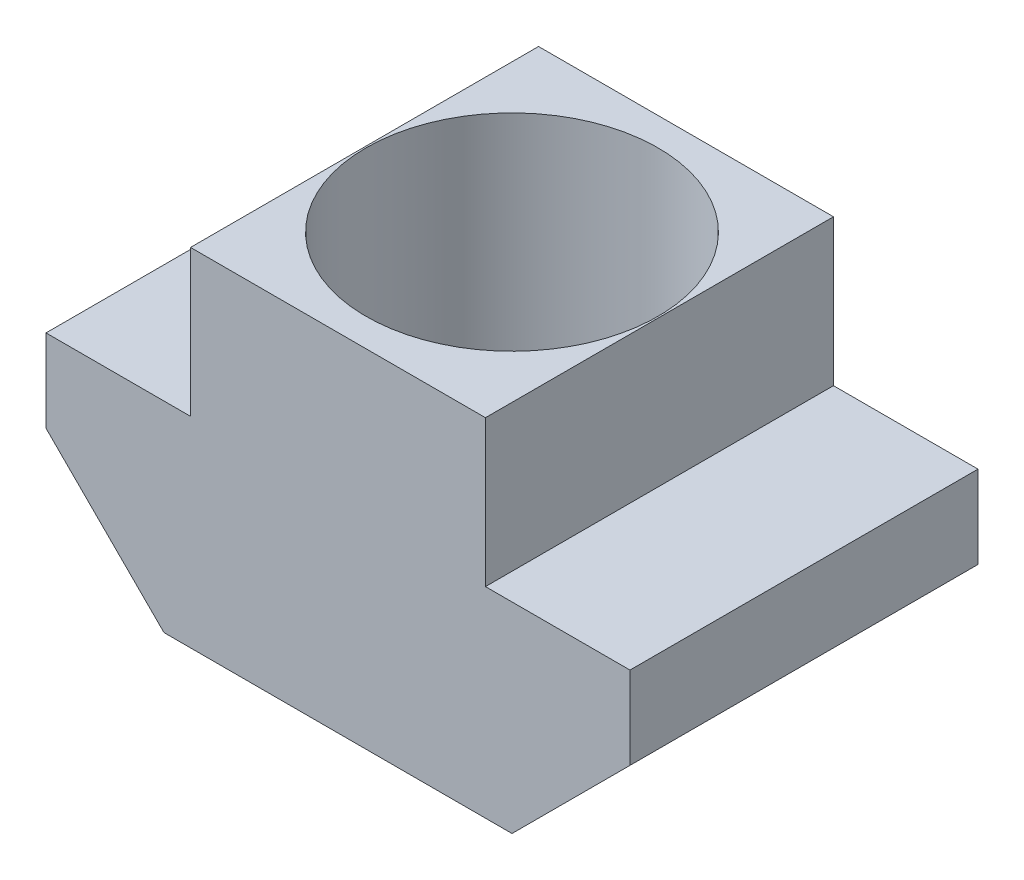
SolidWorks part; units mm, degrees
ref_plane "Front Plane" through (0, 0, 0) normal (0, 0, 1) x (1, 0, 0)
ref_plane "Top Plane" through (0, 0, 0) normal (0, 1, 0) x (1, 0, 0)
ref_plane "Right Plane" through (0, 0, 0) normal (1, 0, 0) x (0, 0, -1)
sketch "Sketch1" plane through (0, 0, 0) normal (0, 0, 1) x (1, 0, 0)
  line L12 (4.95, 0.3) -> (2.95, -1.7)
  line L13 (2.95, -1.7) -> (-2.95, -1.7)
  line L14 (4.95, 0.3) -> (4.95, 1.7)
  line L15 (4.95, 1.7) -> (2.5, 1.7)
  line L16 (-4.95, 0.3) -> (-4.95, 1.7)
  line L17 (4.95, -1.7) -> (-4.95, 1.7) construction
  line L18 (4.95, 1.7) -> (-4.95, -1.7) construction
  line L19 (-2.95, -1.7) -> (-4.95, 0.3)
  line L20 (0, 0) -> (0, 4.908) construction
  line L21 (-2.5, 1.7) -> (-4.95, 1.7)
  line L22 (2.5, 4.18) -> (-2.5, 4.18)
  line L23 (2.5, 4.18) -> (2.5, 1.7)
  line L25 (-2.5, 4.18) -> (-2.5, 1.7)
  line L26 (2.5, 4.18) -> (-2.5, 1.7) construction
  line L27 (2.5, 1.7) -> (-2.5, 4.18) construction
  point P0 (0, 0)
  point P14 (0, 2.94)
  dimension "D2" = 3.4
  dimension "D1" = 9.9
  dimension "D5" = 5
  dimension "D6" = 2.48
extrude "Boss-Extrude1" add sketch "Sketch1" along normal blind 5.9
sketch "Sketch2" plane through (0, 4.18, 0) normal (0, 1, 0) x (1, 0, 0)
  line L0 (2.5, 0) -> (-2.5, 0) construction
  circle A0 centre (0, -2.95) radius 2.475
  dimension "D2" = 4.95
  dimension "D1" = 2.95
extrude "Cut-Extrude7" cut sketch "Sketch2" against normal through all
sketch "Sketch3" plane through (0, 4.18, 0) normal (0, 1, 0) x (1, 0, 0)
  circle A0 centre (0, -2.95) radius 2.475
  circle A1 centre (0, -2.95) radius 2.475 construction
